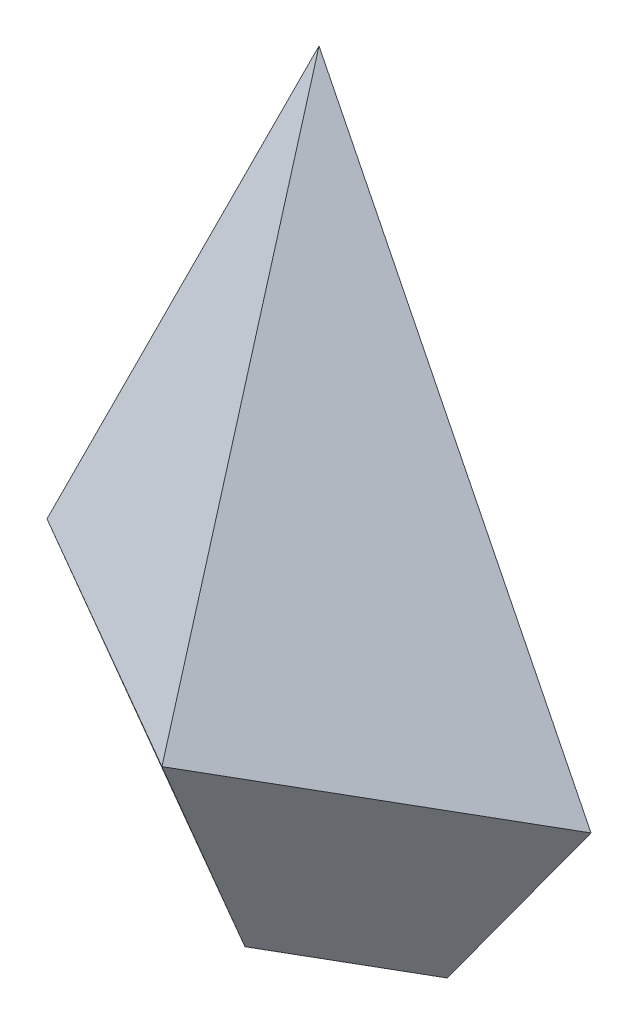
SolidWorks part; units mm, degrees
ref_plane "Спереди" through (0, 0, 0) normal (0, 0, 1) x (1, 0, 0)
ref_plane "Сверху" through (0, 0, 0) normal (0, 1, 0) x (1, 0, 0)
ref_plane "Справа" through (0, 0, 0) normal (1, 0, 0) x (0, 0, -1)
sketch "Эскиз1" plane through (0, 0, 0) normal (0, 1, 0) x (1, 0, 0)
  line L0 (0, 22.6785) -> (0, -15) construction
  line L1 (-25.9808, 0) -> (43.4821, 0) construction
  line L2 (-25.9808, 0) -> (0, -15)
  line L3 (0, -15) -> (25.9808, 0)
  line L4 (0, 15) -> (25.9808, 0)
  line L5 (-25.9808, 0) -> (0, 15)
  circle A0 centre (0, 0) radius 11.7752 construction
  dimension "D1" = 30
  dimension "D2" = 30
  dimension "D3" = 30
extrude "Бобышка-Вытянуть1" add sketch "Эскиз1" along normal blind 40 draft 20
sketch "Эскиз2" plane through (0, 40, 0) normal (0, 1, 0) x (1, 0, 0)
  line L0 (-55.0984, 0) -> (0, -31.8111)
  line L1 (0, -31.8111) -> (55.0984, 0)
  line L2 (55.0984, 0) -> (0, 31.8111)
  line L3 (0, 31.8111) -> (-55.0984, 0)
extrude "Бобышка-Вытянуть2" add sketch "Эскиз2" along normal blind 200 draft 14
sketch "Эскиз3" plane through (0, 0, 0) normal (0, -1, 0) x (1, 0, 0)
  circle A0 centre (0, 0) radius 10.005
  dimension "D1" = 20.01
extrude "Вырез-Вытянуть1" cut sketch "Эскиз3" against normal blind 50
